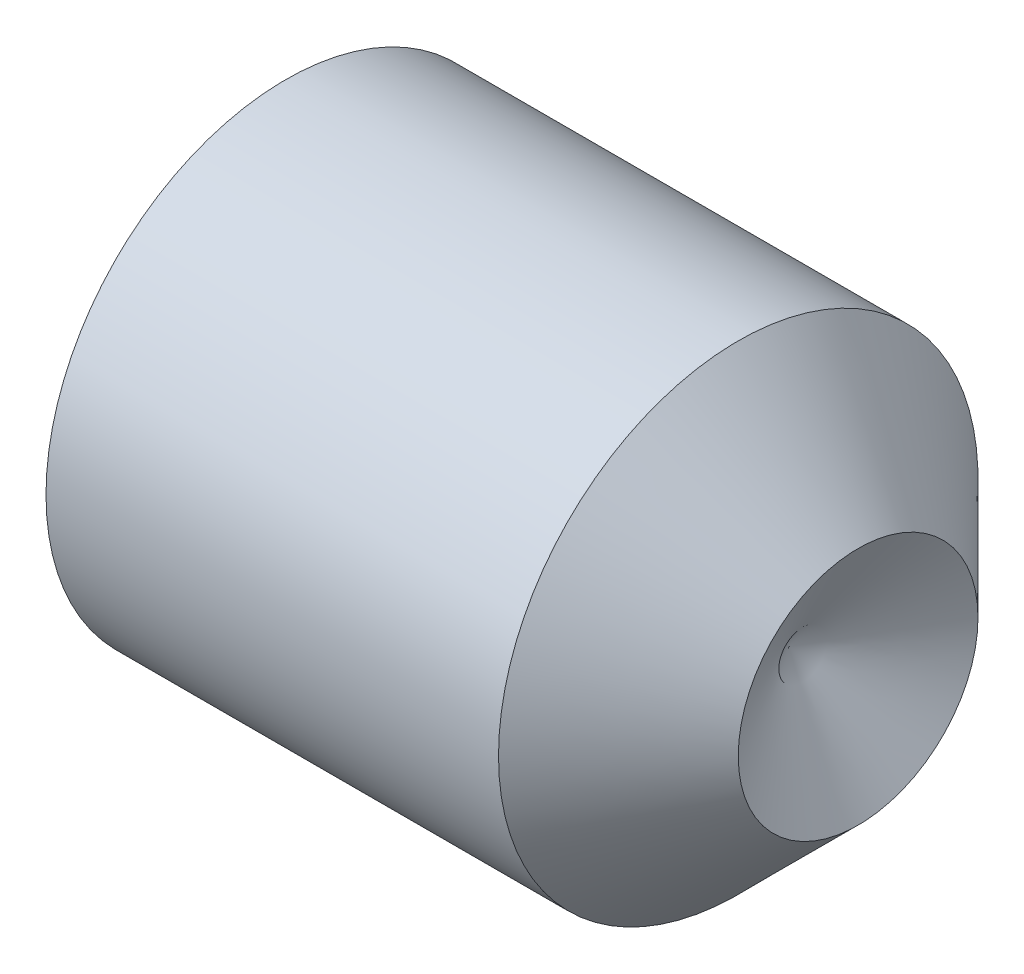
SolidWorks part; units mm, degrees
revolve "BaseBody" add sketch "BodySke" angle 360 about L5
sketch "BodySke" plane through (0, 0, 0) normal (0, 0, 1) x (1, 0, 0)
  line L0 (0, 0) -> (0, 1.61)
  line L1 (0, 1.61) -> (0.2252, 2)
  line L2 (0.2252, 2) -> (4, 2)
  line L3 (4, 2) -> (5, 1)
  line L4 (4.4226, 0) -> (0, 0)
  line L5 (-12.7, 0) -> (88.9, 0) construction
  line L6 (4.4226, 0) -> (5, 1)
  line L7 (5, 1) -> (5, 10.525) construction
  line L8 (0, -1.61) -> (0.2252, -2) construction
  line L9 (4.4226, 0) -> (5, -1) construction
  line L10 (4, -2) -> (5, -1) construction
  line L11 (0.35, 15.875) -> (0.35, -3.175) construction
  dimension "Drive_ch_ang" = 60
  dimension "Cup_ang" = 120
  dimension "Length" = 5
  dimension "Cup_nose_ang" = 45
cosmetic thread "ThreadCosmetic" [suppressed] parameters "Thread_minor"=2.439
ref_plane "Plane1" through (0, 0, 0) normal (0, 0, 1) x (1, 0, 0)
ref_plane "Plane2" through (0, 0, 0) normal (0, 1, 0) x (1, 0, 0)
ref_plane "Plane3" through (0, 0, 0) normal (1, 0, 0) x (0, 0, -1)
sketch "Sketch2" plane through (0, 0, 0) normal (-1, 0, 0) x (0, 0, 1)
  line L0 (0.5774, 1) -> (-0.5774, 1)
  line L1 (-0.5774, 1) -> (-1.1547, 0)
  line L2 (0.5774, 1) -> (1.1547, 0)
  line L3 (0.5774, -1) -> (1.1547, 0)
  line L4 (0.5774, -1) -> (-0.5774, -1)
  line L5 (-0.5774, -1) -> (-1.1547, 0)
  dimension "D2" = 0.75
  dimension "D3" = 0.75
extrude "Hex" cut sketch "Sketch2" against normal blind 1.5
sketch "ThdSchSke" plane through (0, 0, 0) normal (0, 0, 1) x (1, 0, 0)
  line L0 (0.2252, -1.61) -> (-0.0479, -2)
  line L1 (0.2252, -1.61) -> (0.4982, -2)
  line L2 (0.4982, -2) -> (0.4982, -2.5)
  line L3 (-3.175, 0) -> (5.1513, 0) construction
  line L4 (0.2252, 2) -> (0.2252, -2) construction
  line L5 (0.4982, -2.5) -> (-0.0479, -2.5)
  line L6 (-0.0479, -2.5) -> (-0.0479, -2)
  dimension "Thread_minor" = 2.439
  dimension "Diameter" = 3
revolve "ThreadSchematic" [suppressed] cut sketch "ThdSchSke" angle 360 about L3
pattern_linear "ThdSchPat" [suppressed]
equation "\"D2@Sketch2\" = \"Hex_size@Sketch2\" / 2"
equation "\"D3@Sketch2\" = \"Hex_size@Sketch2\" / 2"
equation "\"Thread_minor@ThreadCosmetic\" = \"Minor_dia@BodySke\""
equation "\"Thread_minor@ThdSchSke\" = \"Thread_minor@ThreadCosmetic\""
equation "\"Diameter@ThdSchSke\" = \"Diameter@BodySke\""
equation "\"Overcut@ThdSchSke\" = \"Diameter@BodySke\" * 1.25"
equation "\"Num_threads@ThdSchPat\" = int( (\"Length@BodySke\" - ( ( ( \"Diameter@BodySke\" - \"Minor_dia@BodySke\" ) * 0.5 ) / tan( \"Drive_ch_ang@BodySke\" * 0.017453292 ) ) - ( ( ( \"Diameter@BodySke\" - \"Cup_dia@BodySke\" ) * 0.5 ) * tan( \"Cup_nose_ang@BodySke\" * 0.017453292 ) ) ) / \"Advance@BodySke\" + 0.999 )  + 1"
equation "\"Advance@ThdSchPat\" = (\"Length@BodySke\" - ( ( ( \"Diameter@BodySke\" - \"Minor_dia@BodySke\" ) * 0.5 ) / tan( \"Drive_ch_ang@BodySke\" * 0.017453292 ) ) - ( ( ( \"Diameter@BodySke\" - \"Cup_dia@BodySke\" ) * 0.5 ) * tan( \"Cup_nose_ang@BodySke\" * 0.017453292 ) ) ) /  (\"Num_threads@ThdSchPat\" - 1) 'relax it"
equation "' \"Num_threads@ThdSchPat\" = \"Num_threads@ThdSchPat\" - sgn( \"Num_threads@ThdSchPat\" - 1) '---chamfered tips only---"
